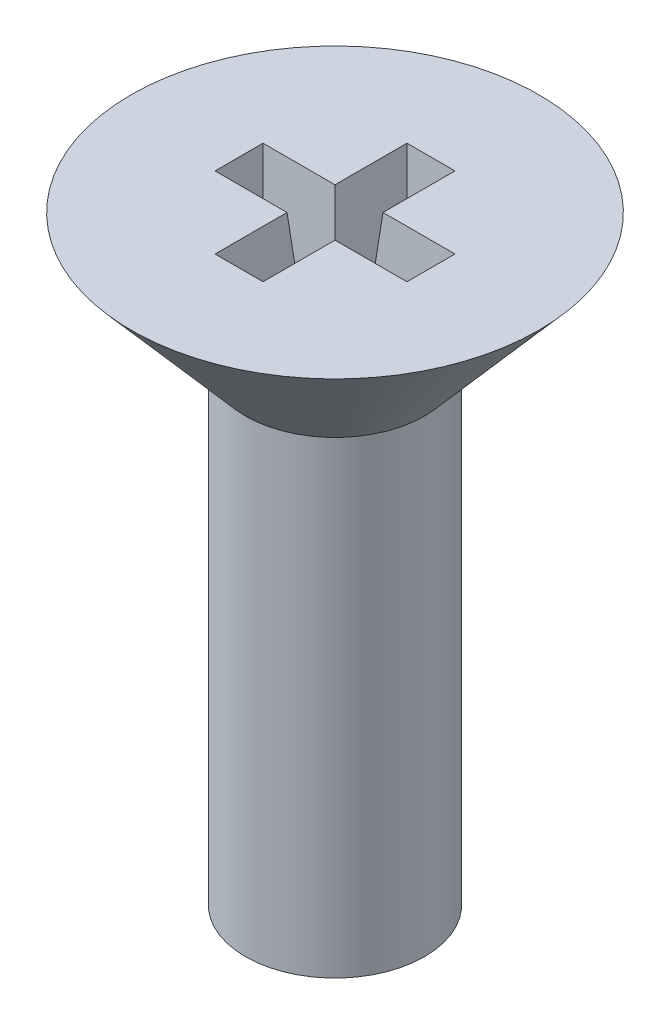
SolidWorks part; units mm, degrees
ref_plane "Front Plane" through (0, 0, 0) normal (0, 0, 1) x (1, 0, 0)
ref_plane "Top Plane" through (0, 0, 0) normal (0, 1, 0) x (1, 0, 0)
ref_plane "Right Plane" through (0, 0, 0) normal (1, 0, 0) x (0, 0, -1)
sketch "Sketch1" plane through (0, 0, 0) normal (0, 0, 1) x (1, 0, 0)
  line L1 (1.4224, 0) -> (3.2385, 2.0892)
  line L5 (3.2385, 2.0892) -> (0, 2.0892)
  line L6 (0, 2.0892) -> (0, 0)
  line L7 (0, 0) -> (0, -7.4358)
  line L8 (0, -7.4358) -> (1.4224, -7.4358)
  line L9 (1.4224, -7.4358) -> (1.4224, 0)
  line L11 (1.4224, 0) -> (0, 0) construction
  dimension "D1" = 9.525
  dimension "D2" = 1.4224
  dimension "D3" = 41
  dimension "D4" = 3.2385
revolve "Revolve1" add sketch "Sketch1" angle 360 about L7
sketch "Sketch2" plane through (0, 2.0892, 0) normal (0, 1, 0) x (1, 0, 0)
  line L0 (-0.381, 1.524) -> (0.381, 1.524)
  line L1 (0.381, 1.524) -> (0.381, 0.381)
  line L2 (0.381, 0.381) -> (1.524, 0.381)
  line L3 (1.524, 0.381) -> (1.524, -0.381)
  line L4 (1.524, -0.381) -> (0.381, -0.381)
  line L5 (0.381, -0.381) -> (0.381, -1.524)
  line L6 (0.381, -1.524) -> (-0.381, -1.524)
  line L7 (-0.381, -1.524) -> (-0.381, -0.381)
  line L8 (-0.381, -0.381) -> (-1.524, -0.381)
  line L9 (-1.524, -0.381) -> (-1.524, 0.381)
  line L10 (-1.524, 0.381) -> (-0.381, 0.381)
  line L11 (-0.381, 0.381) -> (-0.381, 1.524)
  line L12 (0, 1.524) -> (0, 0) construction
  line L13 (0, 0) -> (1.524, 0) construction
  line L15 (0, -1.524) -> (0, 0) construction
  line L16 (-1.524, 0) -> (0, 0) construction
  dimension "D1" = 0.762
  dimension "D2" = 1.524
extrude "Cut-Extrude1" cut sketch "Sketch2" against normal blind 2.159 draft 5
